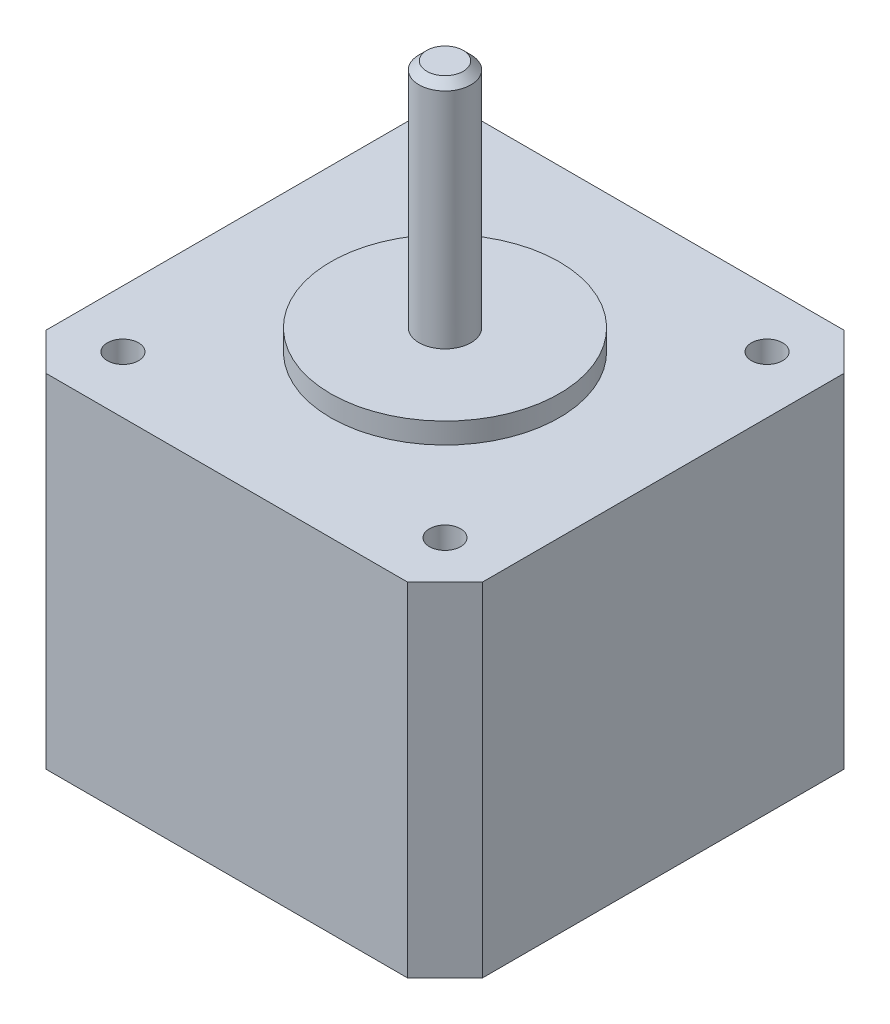
SolidWorks part; units mm, degrees
ref_plane "Front Plane" through (0, 0, 0) normal (0, 0, 1) x (1, 0, 0)
ref_plane "Top Plane" through (0, 0, 0) normal (0, 1, 0) x (1, 0, 0)
ref_plane "Right Plane" through (0, 0, 0) normal (1, 0, 0) x (0, 0, -1)
sketch "Sketch1" plane through (0, 0, 0) normal (0, 1, 0) x (1, 0, 0)
  line L1 (-21, 21) -> (21, 21)
  line L2 (-21, 21) -> (-21, -21)
  line L3 (-21, -21) -> (21, -21)
  line L4 (21, 21) -> (21, -21)
  line L5 (-21, 21) -> (21, -21) construction
  line L6 (-21, -21) -> (21, 21) construction
  point P0 (0, 0)
  dimension "D1" = 42
extrude "Boss-Extrude1" add sketch "Sketch1" along normal blind 33
sketch "Sketch2" plane through (0, 33, 0) normal (0, 1, 0) x (1, 0, 0)
  circle A0 centre (0, 0) radius 11
  dimension "D1" = 22
extrude "Boss-Extrude2" add sketch "Sketch2" along normal blind 2
sketch "Sketch3" plane through (0, 35, 0) normal (0, 1, 0) x (1, 0, 0)
  circle A0 centre (0, 0) radius 2.5
  dimension "D1" = 5
extrude "Boss-Extrude3" add sketch "Sketch3" along normal blind 22.25
chamfer "Chamfer1" distance 3.6 angle 45 4 edges at (-21, 16.5, 21) (21, 16.5, 21) (21, 16.5, -21) (-21, 16.5, -21)
sketch "Sketch4" plane through (0, 33, 0) normal (0, 1, 0) x (1, 0, 0)
  line L1 (-15.5, -15.5) -> (15.5, -15.5) construction
  line L2 (-15.5, -15.5) -> (-15.5, 15.5) construction
  line L3 (-15.5, 15.5) -> (15.5, 15.5) construction
  line L4 (15.5, -15.5) -> (15.5, 15.5) construction
  line L5 (-15.5, -15.5) -> (15.5, 15.5) construction
  line L6 (-15.5, 15.5) -> (15.5, -15.5) construction
  circle A0 centre (15.5, 15.5) radius 1.5
  circle A1 centre (15.5, -15.5) radius 1.5
  circle A2 centre (-15.5, -15.5) radius 1.5
  circle A3 centre (-15.5, 15.5) radius 1.5
  point P0 (0, 0)
  dimension "D2" = 3
  dimension "D1" = 31
extrude "Cut-Extrude1" cut sketch "Sketch4" against normal blind 5
chamfer "Chamfer2" distance 0.75 angle 45 1 edges at (0, 57.25, 2.5)
